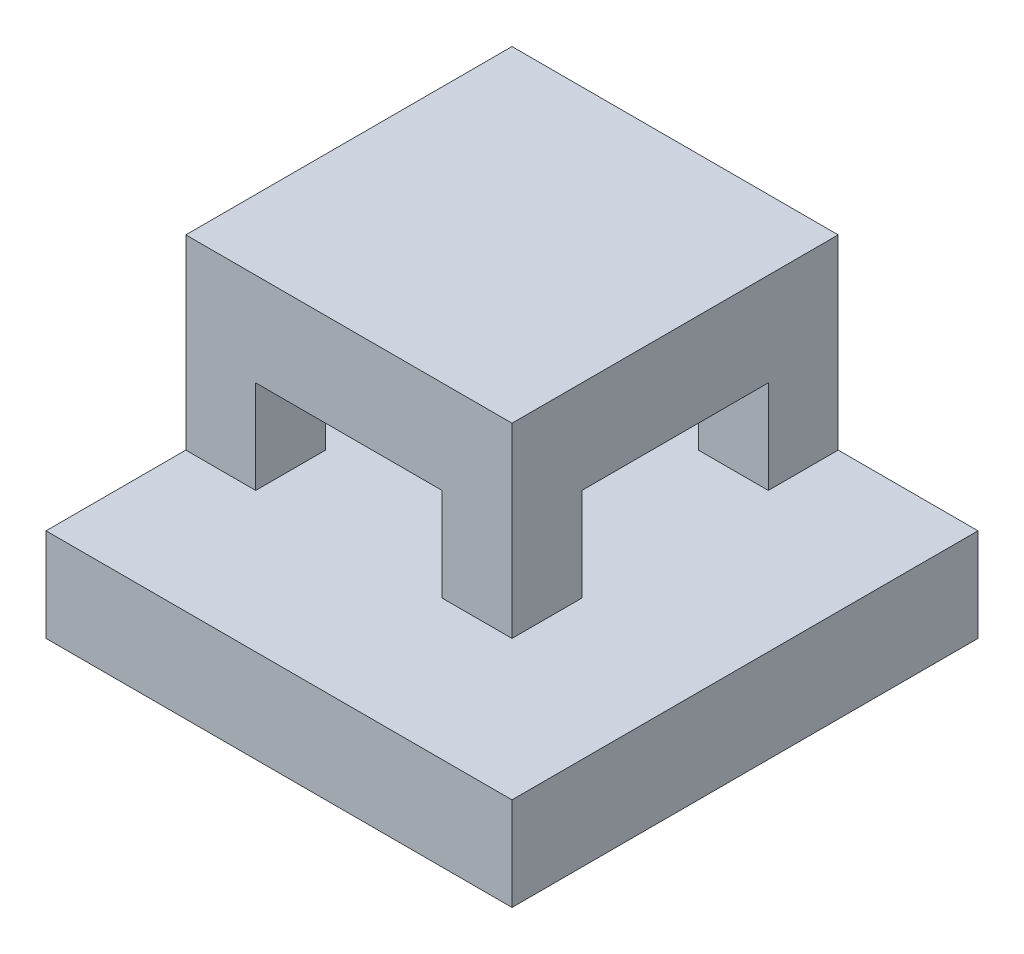
SolidWorks part; units mm, degrees
ref_plane "Alzado" through (0, 0, 0) normal (0, 0, 1) x (1, 0, 0)
ref_plane "Planta" through (0, 0, 0) normal (0, 1, 0) x (1, 0, 0)
ref_plane "Vista lateral" through (0, 0, 0) normal (1, 0, 0) x (0, 0, -1)
sketch "Croquis1" plane through (0, 0, 0) normal (0, 1, 0) x (1, 0, 0)
  line L1 (-50, -50) -> (50, -50)
  line L2 (-50, -50) -> (-50, 50)
  line L3 (-50, 50) -> (50, 50)
  line L4 (50, -50) -> (50, 50)
  line L5 (-50, -50) -> (50, 50) construction
  line L6 (-50, 50) -> (50, -50) construction
  point P0 (0, 0)
  dimension "D1" = 100
  dimension "D2" = 100
extrude "Saliente-Extruir1" add sketch "Croquis1" along normal blind 20
sketch "Croquis2" plane through (0, 20, 0) normal (0, 1, 0) x (1, 0, 0)
  line L0 (-50, -20) -> (-35, -20)
  line L1 (-50, -20) -> (-50, -5)
  line L2 (-50, -5) -> (-35, -5)
  line L3 (-50, 35) -> (-35, 35)
  line L4 (-50, 35) -> (-50, 50)
  line L5 (-50, 50) -> (-35, 50)
  line L6 (-35, 35) -> (-35, 50)
  line L7 (-50, 35) -> (-35, 50) construction
  line L12 (-50, 50) -> (-35, 35) construction
  line L13 (-35, -20) -> (-35, -5)
  line L14 (-50, -20) -> (-35, -5) construction
  line L15 (-50, -5) -> (-35, -20) construction
  line L16 (5, 35) -> (20, 35)
  line L17 (5, 35) -> (5, 50)
  line L18 (5, 50) -> (20, 50)
  line L19 (20, 35) -> (20, 50)
  line L20 (5, 35) -> (20, 50) construction
  line L21 (5, 50) -> (20, 35) construction
  line L22 (5, -20) -> (20, -20)
  line L23 (5, -20) -> (5, -5)
  line L24 (5, -5) -> (20, -5)
  line L25 (20, -20) -> (20, -5)
  line L26 (5, -20) -> (20, -5) construction
  line L27 (5, -5) -> (20, -20) construction
  line L28 (50, 50) -> (-50, 50) construction
  line L29 (-50, 50) -> (-50, -50) construction
  point P0 (-42.5, -12.5)
  point P5 (12.5, 42.5)
  point P6 (-42.5, 42.5)
  point P16 (12.5, -12.5)
  point P23 (5.5397, 42.5)
  point P24 (-34.4084, 3.433)
  point P25 (13.0397, 4.3693)
  dimension "D1" = 15
  dimension "D2" = 15
  dimension "D3" = 15
  dimension "D4" = 15
  dimension "D5" = 15
  dimension "D6" = 15
  dimension "D7" = 15
  dimension "D8" = 15
  dimension "D9" = 70
  dimension "D10" = 70
extrude "Saliente-Extruir2" add sketch "Croquis2" along normal blind 20
sketch "Croquis3" plane through (0, 40, 0) normal (0, 1, 0) x (1, 0, 0)
  line L0 (-50, 50) -> (20, -20) construction
  line L1 (20, 50) -> (-50, -20) construction
  line L3 (-50, -20) -> (20, -20)
  line L4 (-50, -20) -> (-50, 50)
  line L5 (-50, 50) -> (20, 50)
  line L6 (20, -20) -> (20, 50)
  line L7 (-50, -20) -> (20, 50) construction
  line L8 (-50, 50) -> (20, -20) construction
  point P8 (-15, 15)
extrude "Saliente-Extruir3" add sketch "Croquis3" along normal blind 20
